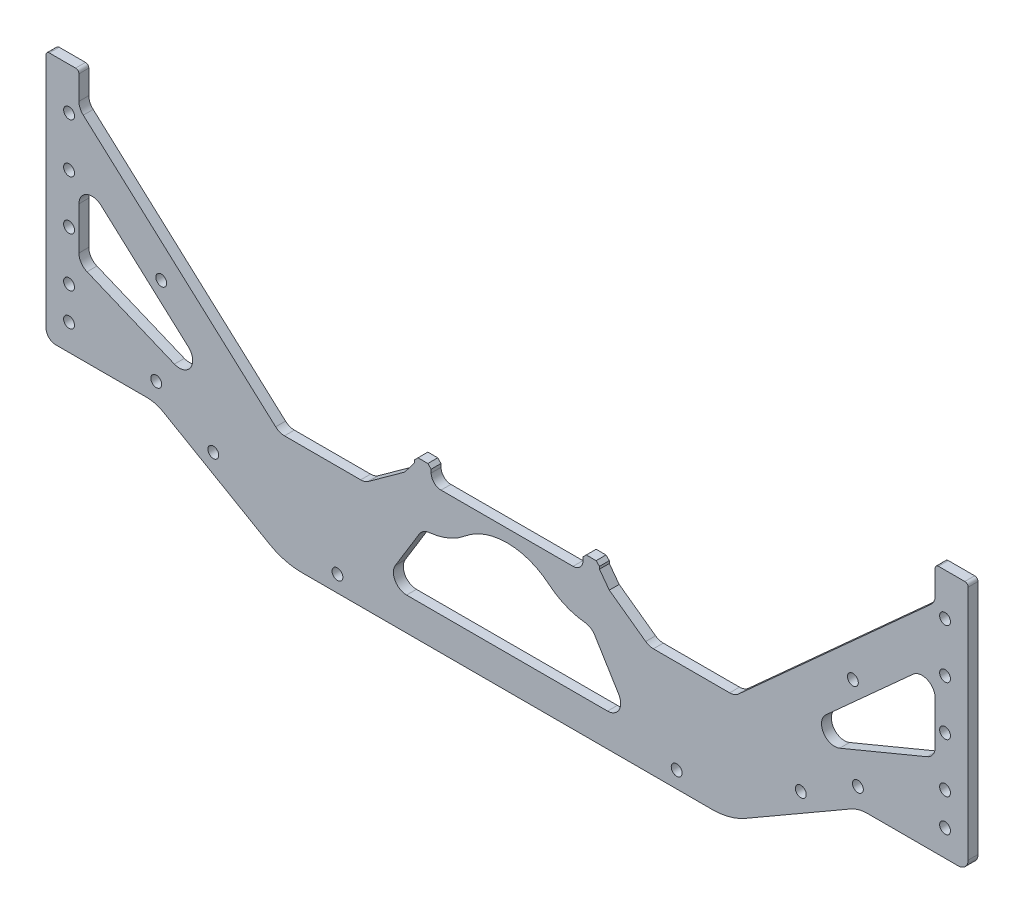
SolidWorks part; units mm, degrees
material "Thornel Mat VMA"
ref_plane "前视基准面" through (0, 0, 0) normal (0, 0, 1) x (1, 0, 0)
ref_plane "上视基准面" through (0, 0, 0) normal (0, 1, 0) x (1, 0, 0)
ref_plane "右视基准面" through (0, 0, 0) normal (1, 0, 0) x (0, 0, -1)
sketch "草图1" plane through (0, 0, 0) normal (0, 0, 1) x (1, 0, 0)
  line L0 (0, 0) -> (53, 0) construction
  line L1 (26.5, 0) -> (26.5, 36.4986) construction
  line L2 (91.5, 5) -> (-38.5, 5)
  line L3 (-38.5, 5) -> (-103.5, 42.5278)
  line L4 (-103.5, 42.5278) -> (-108.5, 33.8675)
  line L5 (-108.5, 33.8675) -> (-41.1795, -5)
  line L6 (-41.1795, -5) -> (94.1795, -5)
  line L7 (161.5, 33.8675) -> (94.1795, -5)
  line L8 (156.5, 42.5278) -> (161.5, 33.8675)
  line L9 (91.5, 5) -> (156.5, 42.5278)
  circle A0 centre (0, 0) radius 1.65
  circle A1 centre (53, 0) radius 1.65
  circle A2 centre (53, 0) radius 1.65
  point P17 (26.5, -5)
  point P20 (26.5, 5)
  dimension "D1" = 3.3
  dimension "D2" = 3.3
  dimension "D3" = 53
  dimension "D7" = 5
  dimension "D4" = 65
  dimension "D5" = 65
  dimension "D6" = 10
  dimension "D8" = 10
  dimension "D9" = 150
extrude "凸台-拉伸1" add sketch "草图1" along normal blind 3 contours L9 L2 L3 L4 L5 L6 L7 L8 A1 A0
fillet "圆角1" radius 20 4 edges at (94.1795, -5, 1.5) (91.5, 5, 1.5) (-41.1795, -5, 1.5) (-38.5, 5, 1.5)
sketch "草图2" plane through (0, 0, 3) normal (0, 0, 1) x (1, 0, 0)
  line L0 (-99.1343, 34.2337) -> (-40.4103, 0.3294) construction
  line L1 (-108.5, 33.8675) -> (-45.8205, -2.3205) construction
  line L2 (-43.141, 7.6795) -> (-103.5, 42.5278) construction
  line L3 (-103.5, 42.5278) -> (-108.5, 33.8675) construction
  line L4 (26.5, 5) -> (26.5, 36.9406) construction
  line L5 (86.141, 5) -> (-33.141, 5) construction
  circle A1 centre (-62.6987, 13.1976) radius 1.65
  circle A2 centre (-80.0192, 23.1976) radius 1.65
  circle A3 centre (133.0192, 23.1976) radius 1.65
  circle A4 centre (115.6987, 13.1976) radius 1.65
  circle A6 centre (-25, 0) radius 1.65
  circle A7 centre (0, 0) radius 1.65 construction
  circle A8 centre (78, 0) radius 1.65
  dimension "D2" = 3.3
  dimension "D3" = 3.3
  dimension "D4" = 3.3
  dimension "D5" = 30
  dimension "D6" = 20
  dimension "D7" = 25
  dimension "D1" = 5
extrude "切除-拉伸1" cut sketch "草图2" against normal blind 10
sketch "草图3" plane through (0, 0, 3) normal (0, 0, 1) x (1, 0, 0)
  line L0 (-103.5, 42.5278) -> (-13.141, 5)
  line L1 (-43.141, 7.6795) -> (-103.5, 42.5278) construction
  line L2 (86.141, 5) -> (-33.141, 5) construction
  line L3 (-13.141, 5) -> (-33.141, 5)
  line L4 (-43.141, 7.6795) -> (-103.5, 42.5278)
  line L5 (26.5, 5) -> (26.5, 26.1465) construction
  line L6 (156.5, 42.5278) -> (66.141, 5)
  line L7 (96.141, 7.6795) -> (156.5, 42.5278)
  line L8 (66.141, 5) -> (86.141, 5)
  arc A0 (-43.141, 7.6795) -> (-33.141, 5) centre (-33.141, 25) ccw construction
  arc A1 (-43.141, 7.6795) -> (-33.141, 5) centre (-33.141, 25) ccw
  arc A2 (96.141, 7.6795) -> (86.141, 5) centre (86.141, 25) cw
  dimension "D1" = 20
extrude "凸台-拉伸2" add sketch "草图3" against normal up to vertex (3 mm away)
fillet "圆角2" radius 10 2 edges at (66.141, 5, 1.5) (-13.141, 5, 1.5)
sketch "草图4" plane through (0, 0, 3) normal (0, 0, 1) x (1, 0, 0)
  line L0 (-103.5, 42.5278) -> (-108.5, 33.8675)
  line L1 (-108.5, 33.8675) -> (-80.1987, 17.5278)
  line L2 (-108.5, 33.8675) -> (-45.8205, -2.3205) construction
  line L3 (-80.1987, 17.5278) -> (-113.5, 17.5278)
  line L4 (-113.5, 17.5278) -> (-113.5, 42.5278)
  line L5 (-113.5, 42.5278) -> (-103.5, 42.5278)
  line L6 (26.5, 5) -> (26.5, 66.9816) construction
  line L7 (64.147, 5) -> (-11.147, 5) construction
  line L8 (166.5, 17.5278) -> (166.5, 42.5278)
  line L9 (133.1987, 17.5278) -> (166.5, 17.5278)
  line L10 (161.5, 33.8675) -> (133.1987, 17.5278)
  line L11 (156.5, 42.5278) -> (161.5, 33.8675)
  line L12 (166.5, 42.5278) -> (156.5, 42.5278)
  dimension "D1" = 25
  dimension "D2" = 10
extrude "凸台-拉伸3" add sketch "草图4" against normal up to surface (3 mm away) up to face at (26.5, 13.1653, 0)
fillet "圆角3" radius 10 2 edges at (133.1987, 17.5278, 1.5) (-80.1987, 17.5278, 1.5)
fillet "圆角4" radius 3 4 edges at (166.5, 42.5278, 1.5) (166.5, 17.5278, 1.5) (-113.5, 42.5278, 1.5) (-113.5, 17.5278, 1.5)
sketch "草图6" plane through (0, 0, 3) normal (0, 0, 1) x (1, 0, 0)
  line L0 (26.5, 5) -> (26.5, 46.6071) construction
  line L1 (64.147, 5) -> (-11.147, 5) construction
  line L2 (-103.5, 42.5278) -> (-110.5, 42.5278) construction
  line L3 (-113.5, 39.5278) -> (-113.5, 20.5278) construction
  circle A0 centre (-106.5, 35.5278) radius 1.65
  circle A1 centre (-106.5, 25.5278) radius 1.65
  circle A2 centre (159.5, 25.5278) radius 1.65
  circle A3 centre (159.5, 35.5278) radius 1.65
  dimension "D1" = 3.3
  dimension "D2" = 3.3
  dimension "D3" = 7
  dimension "D4" = 10
  dimension "D5" = 7
extrude "切除-拉伸2" cut sketch "草图6" against normal blind 5
sketch "草图7" plane through (0, 0, 3) normal (0, 0, 1) x (1, 0, 0)
  line L0 (-40.3116, 16.2844) -> (-13.5, 38.782)
  line L1 (-14.9825, 5.7648) -> (-103.5, 42.5278) construction
  line L2 (-13.5, 38.782) -> (26.5, 38.782)
  line L3 (26.5, 5) -> (26.5, 100.835) construction
  line L4 (64.147, 5) -> (-11.147, 5) construction
  line L5 (-33.8837, 8.624) -> (-9.8603, 28.782)
  line L6 (-9.8603, 28.782) -> (26.5, 28.782)
  line L7 (-40.3116, 16.2844) -> (-33.8837, 8.624)
  line L8 (62.8603, 28.782) -> (26.5, 28.782)
  line L9 (86.8837, 8.624) -> (62.8603, 28.782)
  line L10 (66.5, 38.782) -> (26.5, 38.782)
  line L11 (93.3116, 16.2844) -> (66.5, 38.782)
  line L12 (93.3116, 16.2844) -> (86.8837, 8.624)
  dimension "D1" = 140
  dimension "D2" = 35
  dimension "D3" = 40
  dimension "D4" = 10
extrude "凸台-拉伸4" add sketch "草图7" against normal up to surface (3 mm away) up to face at (161.15, 35.5278, 0)
sketch "草图8" plane through (0, 0, 3) normal (0, 0, 1) x (1, 0, 0)
  line L0 (26.5, 5) -> (26.5, 83.5373) construction
  line L1 (64.147, 5) -> (-11.147, 5) construction
  circle A0 centre (-106.5, 25.5278) radius 1.65 construction
  circle A1 centre (-106.5, 35.5278) radius 1.65 construction
  circle A2 centre (-106.5, 25.5278) radius 1.65
  circle A3 centre (-106.5, 35.5278) radius 1.65
  circle A4 centre (-98.5, 35.5278) radius 1.65
  circle A5 centre (-98.5, 25.5278) radius 1.65
  circle A6 centre (151.5, 25.5278) radius 1.65
  circle A7 centre (151.5, 35.5278) radius 1.65
  circle A8 centre (159.5, 35.5278) radius 1.65
  circle A9 centre (159.5, 25.5278) radius 1.65
  dimension "D1" = 2
extrude "切除-拉伸3" cut sketch "草图8" against normal blind 10
sketch "草图9" plane through (0, 0, 3) normal (0, 0, 1) x (1, 0, 0)
  line L0 (-13.5, 38.782) -> (-111.7635, 56.1085)
  line L1 (-111.7635, 56.1085) -> (-113.5, 46.2604)
  line L2 (-113.5, 46.2604) -> (-23.5, 30.391)
  line L3 (-13.5, 38.782) -> (-40.3116, 16.2844) construction
  line L4 (66.5, 38.782) -> (-13.5, 38.782) construction
  line L5 (-106.5, 35.5278) -> (-106.5, 52.0247) construction
  line L6 (-23.5, 30.391) -> (-13.5, 38.782)
  line L7 (26.5, 38.782) -> (26.5, 99.0808) construction
  line L8 (166.5, 46.2604) -> (76.5, 30.391)
  line L9 (164.7635, 56.1085) -> (166.5, 46.2604)
  line L10 (66.5, 38.782) -> (164.7635, 56.1085)
  line L11 (76.5, 30.391) -> (66.5, 38.782)
  line L12 (-113.5, 39.5278) -> (-113.5, 20.5278) construction
  dimension "D3" = 10
  dimension "D4" = 170
extrude "凸台-拉伸5" add sketch "草图9" against normal up to surface (3 mm away) up to face at (153.15, 25.5278, 0)
fillet "圆角5" radius 3 14 edges at (66.5, 38.782, 1.5) (-13.5, 38.782, 1.5) (-23.5, 30.391, 1.5) (-40.3116, 16.2844, 1.5) (-29.9051, 11.9624, 1.5) (-9.8603, 28.782, 1.5) (62.8603, 28.782, 1.5) (82.9051, 11.9624, 1.5) (93.3116, 16.2844, 1.5) (76.5, 30.391, 1.5) (166.5, 46.2604, 1.5) (164.7635, 56.1085, 1.5) (-113.5, 46.2604, 1.5) (-111.7635, 56.1085, 1.5)
sketch "草图10" plane through (0, 0, 3) normal (0, 0, 1) x (1, 0, 0)
  line L0 (174.5, 103.4145) -> (174.5, 73.4145) construction
  line L1 (-121.5, 103.4145) -> (-121.5, 73.4145) construction
  line L2 (-108.9114, 68.9181) -> (-113.5, 62.3649)
  line L3 (-113.5, 62.3649) -> (-102.142, 54.412)
  line L4 (-13.7585, 38.8276) -> (-108.8091, 55.5876) construction
  line L5 (-102.142, 54.412) -> (-83.5, 51.1249)
  line L6 (-83.5, 51.1249) -> (-108.9114, 68.9181)
  line L7 (-113.5, 39.5278) -> (-113.5, 20.5278) construction
  line L8 (26.5, 38.782) -> (26.5, 127.7041) construction
  line L9 (66.2375, 38.782) -> (-13.2375, 38.782) construction
  line L10 (136.5, 51.1249) -> (161.9114, 68.9181)
  line L11 (155.142, 54.412) -> (136.5, 51.1249)
  line L12 (166.5, 62.3649) -> (155.142, 54.412)
  line L13 (161.9114, 68.9181) -> (166.5, 62.3649)
  dimension "D3" = 8
  dimension "D4" = 155
  dimension "D5" = 38
extrude "凸台-拉伸6" add sketch "草图10" against normal up to vertex (3 mm away)
fillet "圆角6" radius 2 8 edges at (161.9114, 68.9181, 1.5) (166.5, 62.3649, 1.5) (155.142, 54.412, 1.5) (136.5, 51.1249, 1.5) (-83.5, 51.1249, 1.5) (-102.142, 54.412, 1.5) (-108.9114, 68.9181, 1.5) (-113.5, 62.3649, 1.5)
sketch "草图11" plane through (0, 0, 3) normal (0, 0, 1) x (1, 0, 0)
  line L0 (26.5, 38.782) -> (26.5, 115.9487) construction
  line L1 (-113.5, 39.5278) -> (-103.5, 39.5278)
  line L2 (-113.5, 39.5278) -> (-113.5, 106.9145)
  line L3 (-113.5, 106.9145) -> (-103.5, 106.9145)
  line L4 (-103.5, 39.5278) -> (-103.5, 106.9145)
  line L5 (66.2375, 38.782) -> (-13.2375, 38.782) construction
  line L6 (156.5, 39.5278) -> (156.5, 106.9145)
  line L7 (166.5, 106.9145) -> (156.5, 106.9145)
  line L8 (166.5, 39.5278) -> (166.5, 106.9145)
  line L9 (166.5, 39.5278) -> (156.5, 39.5278)
  dimension "D2" = 10
extrude "凸台-拉伸7" add sketch "草图11" against normal up to surface (3 mm away) up to face at (153.15, 25.5278, 0)
sketch "草图14" plane through (0, 0, 3) normal (0, 0, 1) x (1, 0, 0)
  line L0 (166.5, 20.5278) -> (166.5, 106.9145) construction
  line L1 (-113.5, 106.9145) -> (166.5, 106.9145)
  line L2 (-113.5, 106.9145) -> (-113.5, 97.32)
  line L3 (-113.5, 97.32) -> (166.5, 97.32)
  line L4 (166.5, 106.9145) -> (166.5, 97.32)
extrude "切除-拉伸6" cut sketch "草图14" against normal blind 30
sketch "草图15" plane through (0, 0, 3) normal (0, 0, 1) x (1, 0, 0)
  line L0 (-65.7779, 48) -> (-55.0521, 39)
  line L1 (-55.0521, 39) -> (108.0521, 39)
  line L2 (108.0521, 39) -> (118.7779, 48)
  line L3 (-13.7585, 38.8276) -> (-83.0633, 51.0479) construction
  line L4 (136.0633, 51.0479) -> (66.7585, 38.8276) construction
  line L5 (-65.7779, 48) -> (118.7779, 48)
  dimension "D1" = 150
  dimension "D2" = 150
  dimension "D3" = 48
  dimension "D4" = 9
extrude "切除-拉伸7" cut sketch "草图15" against normal blind 10
sketch "草图16" plane through (0, 0, 3) normal (0, 0, 1) x (1, 0, 0)
  line L0 (-14.6273, 24.782) -> (67.6273, 24.782)
  line L1 (-26.1219, 15.1369) -> (-10.6967, 28.0801) construction
  line L2 (63.6967, 28.0801) -> (79.1219, 15.1369) construction
  line L3 (67.6273, 24.782) -> (67.6273, 30.782)
  line L4 (67.6273, 30.782) -> (-14.6273, 30.782)
  line L5 (-14.6273, 30.782) -> (-14.6273, 24.782)
  line L6 (-8.7684, 28.782) -> (61.7684, 28.782) construction
  dimension "D1" = 6
  dimension "D2" = 2
extrude "凸台-拉伸8" add sketch "草图16" against normal up to surface (3 mm away) up to face at (26.5, 39.3282, 0)
sketch "草图17" plane through (0, 0, 3) normal (0, 0, 1) x (1, 0, 0)
  line L0 (64.147, 5) -> (-11.147, 5) construction
  line L1 (43.3448, 24.782) -> (9.6552, 24.782)
  line L4 (-14.6273, 24.782) -> (67.6273, 24.782) construction
  arc A0 (43.3448, 24.782) -> (9.6552, 24.782) centre (26.5, 14) ccw
  point P5 (26.5, 5)
  dimension "D1" = 20
  dimension "D2" = 9
extrude "切除-拉伸9" cut sketch "草图17" against normal blind 30
fillet "圆角9" radius 20 2 edges at (43.3448, 24.782, 1.5) (9.6552, 24.782, 1.5)
sketch "草图19" plane through (0, 0, 3) normal (0, 0, 1) x (1, 0, 0)
  line L0 (-65.7779, 48) -> (-13.7585, 38.8276)
  line L1 (-13.7585, 38.8276) -> (-55.0521, 39)
  line L2 (-55.0521, 39) -> (-65.7779, 48)
  line L3 (118.7779, 48) -> (66.7585, 38.8276)
  line L4 (66.7585, 38.8276) -> (108.0521, 39)
  line L5 (108.0521, 39) -> (118.7779, 48)
extrude "凸台-拉伸10" add sketch "草图19" against normal up to surface (3 mm away) up to face at (26.5, 16.5292, 0)
sketch "草图20" plane through (0, 0, 3) normal (0, 0, 1) x (1, 0, 0)
  line L0 (-13.7585, 38.8276) -> (-8.0872, 37.8276)
  line L1 (-8.0872, 37.8276) -> (61.0872, 37.8276)
  line L2 (66.7585, 38.8276) -> (61.0872, 37.8276)
  line L3 (66.7585, 38.8276) -> (-13.7585, 38.8276)
  line L4 (136.0633, 51.0479) -> (66.7585, 38.8276) construction
  line L5 (-13.7585, 38.8276) -> (-83.0633, 51.0479) construction
  dimension "D1" = 1
extrude "切除-拉伸10" cut sketch "草图20" against normal blind 10
fillet "圆角11" radius 20 4 edges at (-103.5, 65.129, 1.5) (156.5, 65.129, 1.5) (61.0872, 37.8276, 1.5) (-8.0872, 37.8276, 1.5)
sketch "草图21" plane through (0, 0, 3) normal (0, 0, 1) x (1, 0, 0)
  line L0 (81.4284, 26.2556) -> (61.2222, 43.2106)
  line L1 (61.2222, 43.2106) -> (156.5, 75.5404)
  line L2 (156.5, 75.5404) -> (156.5, 42.5278)
  line L3 (156.5, 42.5278) -> (81.4284, 26.2556)
  line L4 (26.5, 37.8276) -> (26.5, 111.5934) construction
  line L5 (-6.3374, 37.8276) -> (59.3374, 37.8276) construction
  line L6 (-103.5, 75.5404) -> (-103.5, 42.5278)
  line L7 (-8.2222, 43.2106) -> (-103.5, 75.5404)
  line L8 (-28.4284, 26.2556) -> (-8.2222, 43.2106)
  line L9 (-103.5, 42.5278) -> (-28.4284, 26.2556)
extrude "切除-拉伸11" cut sketch "草图21" against normal blind 10
sketch "草图22" plane through (0, 0, 3) normal (0, 0, 1) x (1, 0, 0)
  line L0 (-103.5, 72.5278) -> (-41.9946, 16.9834)
  line L1 (-103.5, 42.5278) -> (-103.5, 97.32) construction
  line L2 (-103.5, 72.5278) -> (-103.5, 83.3072)
  line L3 (-103.5, 83.3072) -> (-34.5954, 21.0808)
  line L4 (-13.5, 38.782) -> (-38.9155, 17.4558) construction
  line L5 (-34.5954, 21.0808) -> (-40.3512, 14.7074)
  line L6 (-40.3512, 14.7074) -> (-41.9946, 16.9834)
  line L7 (-110.5, 17.5278) -> (-82.8782, 17.5278) construction
  line L8 (26.5, 37.8276) -> (26.5, 79.7638) construction
  line L9 (-6.3374, 37.8276) -> (59.3374, 37.8276) construction
  line L10 (87.5954, 21.0808) -> (93.3512, 14.7074)
  line L11 (156.5, 83.3072) -> (87.5954, 21.0808)
  line L12 (156.5, 72.5278) -> (156.5, 83.3072)
  line L13 (156.5, 72.5278) -> (94.9946, 16.9834)
  line L14 (93.3512, 14.7074) -> (94.9946, 16.9834)
  dimension "D1" = 8
  dimension "D2" = 55
extrude "凸台-拉伸11" add sketch "草图22" against normal up to vertex (3 mm away)
sketch "草图23" plane through (0, 0, 3) normal (0, 0, 1) x (1, 0, 0)
  line L1 (-34.5954, 21.0808) -> (-13.5, 21.0808)
  line L2 (-34.5954, 21.0808) -> (-34.5954, 38.782)
  line L3 (-34.5954, 38.782) -> (-13.5, 38.782)
  line L4 (-13.5, 21.0808) -> (-13.5, 38.782)
  line L5 (87.5954, 21.0808) -> (66.5, 21.0808)
  line L6 (87.5954, 21.0808) -> (87.5954, 38.782)
  line L7 (87.5954, 38.782) -> (66.5, 38.782)
  line L8 (66.5, 21.0808) -> (66.5, 38.782)
extrude "切除-拉伸12" cut sketch "草图23" against normal blind 10
sketch "草图24" plane through (0, 0, 3) normal (0, 0, 1) x (1, 0, 0)
  line L0 (-6.3374, 37.8276) -> (59.3374, 37.8276) construction
  line L1 (-5.2225, 37.8276) -> (-21.2926, 37.8276)
  line L2 (-5.2225, 37.8276) -> (-5.2225, 42.7678)
  line L3 (-5.2225, 42.7678) -> (-21.2926, 42.7678)
  line L4 (-21.2926, 37.8276) -> (-21.2926, 42.7678)
  line L6 (50.8005, 37.8276) -> (81.4843, 37.8276)
  line L7 (50.8005, 37.8276) -> (50.8005, 45.2991)
  line L8 (50.8005, 45.2991) -> (81.4843, 45.2991)
  line L9 (81.4843, 37.8276) -> (81.4843, 45.2991)
extrude "切除-拉伸13" cut sketch "草图24" against normal blind 10
sketch "草图25" plane through (0, 0, 3) normal (0, 0, 1) x (1, 0, 0)
  line L0 (-19.0382, 21.0808) -> (-13.5, 37.8276)
  line L1 (-13.5, 37.8276) -> (-13.5, 24.782)
  line L2 (-13.5, 24.782) -> (0.9565, 24.782)
  line L3 (0.9565, 24.782) -> (-11.147, 5)
  line L4 (-11.147, 5) -> (-31.0454, 5)
  line L5 (-31.0454, 5) -> (-31.0454, 21.0808)
  line L6 (-34.5954, 21.0808) -> (-19.0382, 21.0808) construction
  line L7 (-31.0454, 21.0808) -> (-19.0382, 21.0808)
  line L8 (26.5, 37.8276) -> (26.5, 63.9565) construction
  line L9 (-13.5, 37.8276) -> (66.5, 37.8276) construction
  line L10 (84.0454, 5) -> (84.0454, 21.0808)
  line L11 (64.147, 5) -> (84.0454, 5)
  line L12 (52.0435, 24.782) -> (64.147, 5)
  line L13 (66.5, 24.782) -> (52.0435, 24.782)
  line L14 (66.5, 37.8276) -> (66.5, 24.782)
  line L15 (72.0382, 21.0808) -> (66.5, 37.8276)
  line L16 (84.0454, 21.0808) -> (72.0382, 21.0808)
extrude "凸台-拉伸12" add sketch "草图25" against normal up to surface (3 mm away) up to face at (135.9982, 44.013, 0)
chamfer "倒角1" distance 10 2 edges at (-13.5, 37.8276, 1.5) (66.5, 37.8276, 1.5)
sketch "草图26" plane through (0, 0, 3) normal (0, 0, 1) x (1, 0, 0)
  line L0 (-16.6398, 28.3333) -> (-19.0382, 21.0808)
  line L1 (-19.0382, 21.0808) -> (-34.5954, 21.0808)
  line L2 (-34.5954, 21.0808) -> (-42.6262, 28.3333)
  line L3 (-34.5954, 21.0808) -> (-103.5, 83.3072) construction
  line L4 (-42.6262, 28.3333) -> (-16.6398, 28.3333)
  line L5 (69.6398, 28.3333) -> (72.0382, 21.0808)
  line L6 (72.0382, 21.0808) -> (87.5954, 21.0808)
  line L7 (87.5954, 21.0808) -> (95.6262, 28.3333)
  line L8 (156.5, 83.3072) -> (87.5954, 21.0808) construction
  line L9 (95.6262, 28.3333) -> (69.6398, 28.3333)
extrude "凸台-拉伸13" add sketch "草图26" against normal up to vertex (3 mm away)
sketch "草图27" plane through (0, 0, 3) normal (0, 0, 1) x (1, 0, 0)
  line L0 (-103.5, 72.5278) -> (-103.5, 67.1381)
  line L1 (-103.5, 42.5278) -> (-103.5, 72.5278) construction
  line L2 (-103.5, 67.1381) -> (-53.0444, 21.5726)
  line L3 (-41.9946, 16.9834) -> (-103.5, 42.5278) construction
  line L4 (-53.0444, 21.5726) -> (-41.9946, 16.9834)
  line L5 (-41.9946, 16.9834) -> (-103.5, 72.5278)
  line L6 (94.9946, 16.9834) -> (156.5, 72.5278)
  line L7 (156.5, 72.5278) -> (156.5, 67.1381)
  line L8 (156.5, 72.5278) -> (156.5, 42.5278) construction
  line L9 (156.5, 67.1381) -> (106.0444, 21.5726)
  line L10 (156.5, 42.5278) -> (94.9946, 16.9834) construction
  line L11 (106.0444, 21.5726) -> (94.9946, 16.9834)
  dimension "D1" = 4
  dimension "D2" = 4
extrude "凸台-拉伸14" add sketch "草图27" against normal up to surface (3 mm away) up to face at (26.5, 36.3285, 0)
fillet "圆角12" radius 4 22 edges at (64.147, 5, 1.5) (52.0435, 24.782, 1.5) (0.9565, 24.782, 1.5) (-11.147, 5, 1.5) (-3.5, 37.8276, 1.5) (-16.6398, 28.3333, 1.5) (-42.6262, 28.3333, 1.5) (-103.5, 83.3072, 1.5) (-113.5, 97.32, 1.5) (-103.5, 97.32, 1.5) (166.5, 97.32, 1.5) (156.5, 97.32, 1.5) (156.5, 83.3072, 1.5) (95.6262, 28.3333, 1.5) (69.6398, 28.3333, 1.5) (56.5, 37.8276, 1.5) (156.5, 67.1381, 1.5) (156.5, 42.5278, 1.5) (106.0444, 21.5726, 1.5) (-103.5, 42.5278, 1.5) (-53.0444, 21.5726, 1.5) (-103.5, 67.1381, 1.5)
sketch "草图28" plane through (0, 0, 3) normal (0, 0, 1) x (1, 0, 0)
  line L0 (26.5, 39.4948) -> (26.5, 106.2631) construction
  line L1 (-106.5, 50.5278) -> (-78.5, 50.5278) construction
  line L2 (-106.5, 35.5278) -> (-106.5, 80.5278) construction
  line L3 (159.5, 35.5278) -> (159.5, 80.5278) construction
  line L4 (-2.2061, 37.8276) -> (55.2061, 37.8276) construction
  line L5 (159.5, 50.5278) -> (131.5, 50.5278) construction
  circle A0 centre (-106.5, 65.5278) radius 1.65
  circle A1 centre (-106.5, 80.5278) radius 1.65
  circle A2 centre (-106.5, 35.5278) radius 1.65 construction
  circle A3 centre (159.5, 80.5278) radius 1.65
  circle A4 centre (159.5, 65.5278) radius 1.65
  circle A5 centre (-106.5, 50.5278) radius 1.65
  circle A6 centre (159.5, 50.5278) radius 1.65
  circle A7 centre (-78.5, 50.5278) radius 1.65
  circle A8 centre (131.5, 50.5278) radius 1.65
  point P18 (26.5, 37.8276)
  dimension "D1" = 3.3
  dimension "D2" = 3.3
  dimension "D3" = 30
  dimension "D4" = 15
  dimension "D5" = 3.3
  dimension "D6" = 3.3
  dimension "D7" = 15
  dimension "D8" = 15
  dimension "D9" = 3.3
  dimension "D10" = 3.3
  dimension "D11" = 28
  dimension "D12" = 28
extrude "切除-拉伸14" cut sketch "草图28" against normal blind 10
sketch "草图29" plane through (0, 0, 3) normal (0, 0, 1) x (1, 0, 0)
  line L1 (-113.5, 93.32) -> (252.5525, 93.32)
  line L2 (-113.5, 93.32) -> (-113.5, 131.3086)
  line L3 (-113.5, 131.3086) -> (252.5525, 131.3086)
  line L4 (252.5525, 93.32) -> (252.5525, 131.3086)
extrude "切除-拉伸15" cut sketch "草图29" against normal blind 10
fillet "圆角13" radius 1 4 edges at (166.5, 93.32, 1.5) (156.5, 93.32, 1.5) (-113.5, 93.32, 1.5) (-103.5, 93.32, 1.5)
sketch "草图30" plane through (0, 0, 3) normal (0, 0, 1) x (1, 0, 0)
  line L1 (-93.9948, 23.0364) -> (-102.2413, 23.0364)
  line L2 (-93.9948, 23.0364) -> (-93.9948, 37.291)
  line L3 (-93.9948, 37.291) -> (-102.2413, 37.291)
  line L4 (-102.2413, 23.0364) -> (-102.2413, 37.291)
  line L5 (148.0703, 21.1315) -> (155.161, 21.1315)
  line L6 (148.0703, 21.1315) -> (148.0703, 37.291)
  line L7 (148.0703, 37.291) -> (155.161, 37.291)
  line L8 (155.161, 21.1315) -> (155.161, 37.291)
extrude "凸台-拉伸15" add sketch "草图30" against normal up to surface (3 mm away) up to face at (-104.85, 80.5278, 0)
sketch "草图31" plane through (0, 0, 3) normal (0, 0, 1) x (1, 0, 0)
  circle A0 centre (0, 0) radius 1.65
  circle A1 centre (53, 0) radius 1.65
extrude "凸台-拉伸16" add sketch "草图31" against normal up to vertex (3 mm away)
sketch "草图32" plane through (0, 0, 0) normal (0, 0, -1) x (-1, 0, 0)
  line L0 (-57.5488, 37.0698) -> (-54.5488, 41.0698)
  line L1 (-54.5488, 41.0698) -> (-54.5488, 42.8276)
  line L2 (-54.5488, 42.8276) -> (-49.5488, 42.8276)
  line L3 (-49.5488, 42.8276) -> (-49.5488, 37.8276)
  line L4 (2.2061, 37.8276) -> (-55.2061, 37.8276) construction
  line L5 (-49.5488, 37.8276) -> (-57.5488, 37.0698)
  line L6 (-26.5, 37.8276) -> (-26.5, 57.0496) construction
  line L7 (-3.4512, 42.8276) -> (-3.4512, 37.8276)
  line L8 (1.5488, 42.8276) -> (-3.4512, 42.8276)
  line L9 (1.5488, 41.0698) -> (1.5488, 42.8276)
  line L10 (4.5488, 37.0698) -> (1.5488, 41.0698)
  line L11 (-3.4512, 37.8276) -> (4.5488, 37.0698)
  dimension "D1" = 8
  dimension "D2" = 5
  dimension "D3" = 4
  dimension "D4" = 5
extrude "凸台-拉伸17" add sketch "草图32" against normal up to surface (3 mm away) up to face at (26.5, 44.0014, 3)
fillet "圆角14" radius 3 2 edges at (3.4512, 37.8276, 1.5) (49.5488, 37.8276, 1.5)
chamfer "倒角2" distance 1 angle 45 4 edges at (54.5488, 42.8276, 1.5) (49.5488, 42.8276, 1.5) (3.4512, 42.8276, 1.5) (-1.5488, 42.8276, 1.5)
